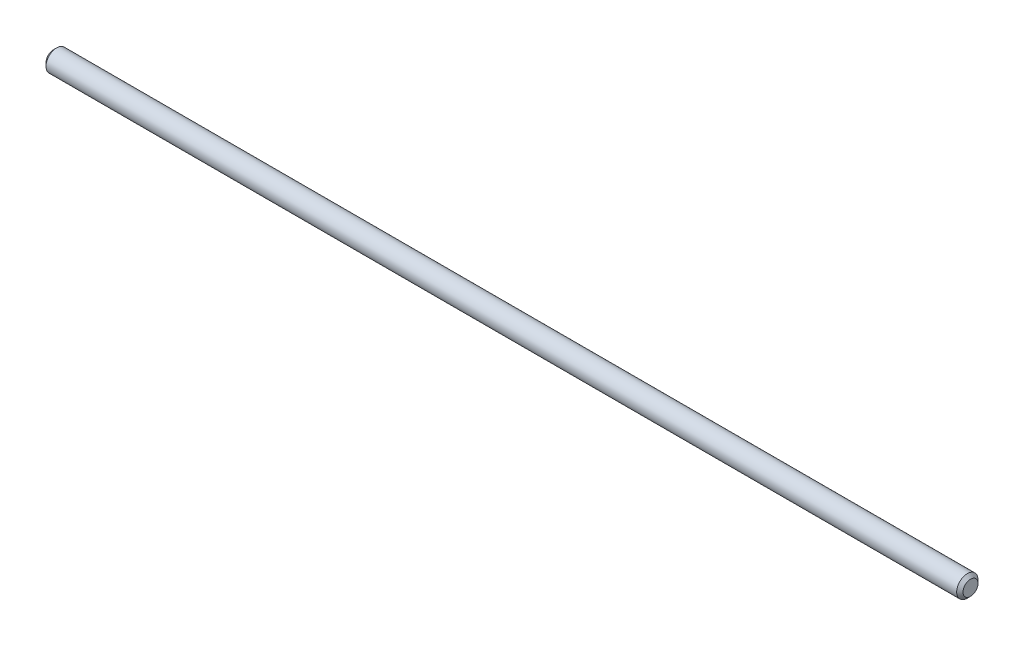
SolidWorks part; units mm, degrees
material "Stainless Steel (ferritic)"
ref_plane "Front Plane" through (0, 0, 0) normal (0, 0, 1) x (1, 0, 0)
ref_plane "Top Plane" through (0, 0, 0) normal (0, 1, 0) x (1, 0, 0)
ref_plane "Right Plane" through (0, 0, 0) normal (1, 0, 0) x (0, 0, -1)
sketch "Sketch1" plane through (0, 0, 0) normal (0, 0, 1) x (1, 0, 0)
  line L0 (-136.525, 0) -> (136.525, 0) construction
  line L1 (136.525, 3.175) -> (136.525, -3.175) construction
  line L2 (-136.525, 3.175) -> (-136.525, -3.175) construction
  line L3 (136.525, 3.175) -> (53.975, 3.175) construction
  point P6 (132.08, -3.175)
  point P9 (-123.825, 0)
  point P10 (123.825, 0)
  point P11 (-98.425, 0)
  point P12 (98.425, 0)
  dimension "D1" = 4.445
  dimension "D2" = 12.7
  dimension "D3" = 12.7
  dimension "D4" = 25.4
  dimension "D5" = 25.4
sketch "Sketch2" plane through (0, 0, 0) normal (1, 0, 0) x (0, 0, -1)
  circle A0 centre (0, 0) radius 3.175
extrude "Boss-Extrude1" add sketch "Sketch2" against normal up to vertex (136.525 mm away) and the other way up to vertex (136.525 mm away) up to point (-136.525, 0, 0) other way up to point (136.525, 0, 0)
chamfer "Chamfer1" distance 0.9525 angle 45 2 edges at (-136.525, 0, -3.175) (136.525, 0, -3.175)
sketch "Drawing1" plane through (0, 0, 0) normal (1, 0, 0) x (0, 0, -1)
  circle A0 centre (0, 0) radius 3.175
equation "\"D2@Sketch1\"=\"Thread Diameter@Sketch1\"*2"
equation "\"D3@Sketch1\"=\"Thread Diameter@Sketch1\"*2"
equation "\"Length@Sketch1\"=12-2.08+0.5+(9-8.67)"
